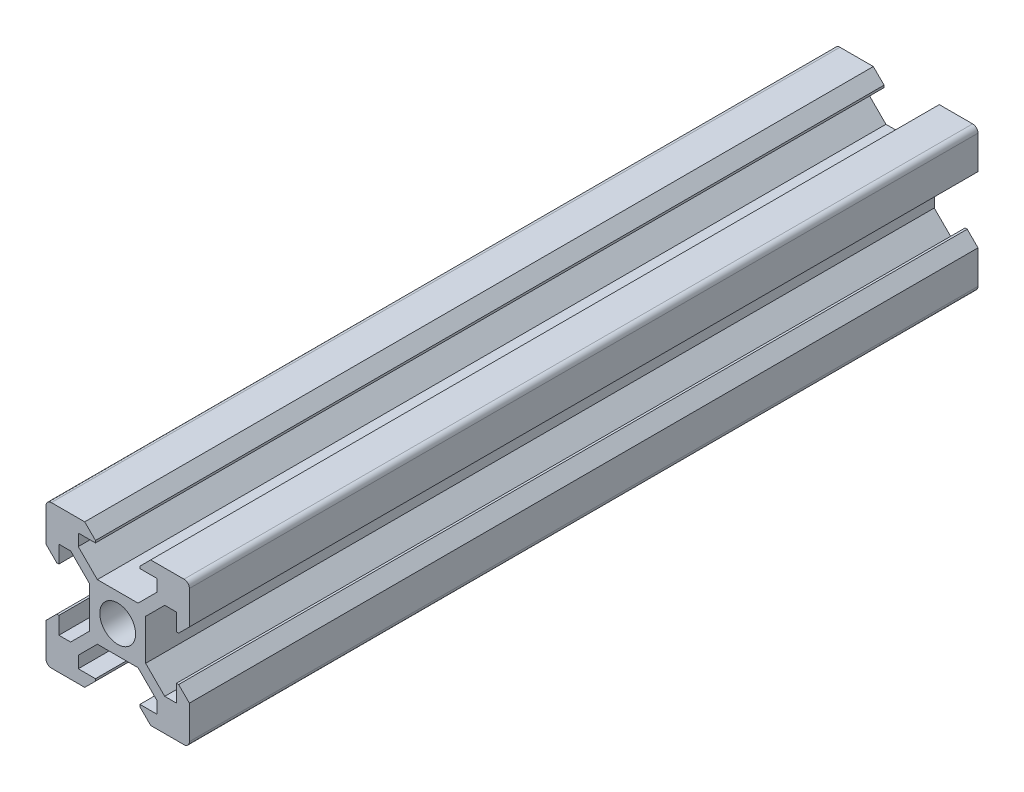
SolidWorks part; units mm, degrees
other "Markup1"
sketch "Sketch1" plane through (10, 10, 480) normal (0.5774, 0.5773, 0.5774) x (0.7071, 0, -0.7071)
ref_plane "Alzado" through (0, 0, 0) normal (0, 0, 1) x (1, 0, 0)
ref_plane "Planta" through (0, 0, 0) normal (0, 1, 0) x (1, 0, 0)
ref_plane "Vista lateral" through (0, 0, 0) normal (1, 0, 0) x (0, 0, -1)
sketch "Croquis1" plane through (0, 0, 0) normal (0, 0, 1) x (1, 0, 0)
  line L0 (-4.6, 10) -> (-3.1, 8.5)
  line L3 (-4.6, 10) -> (-9.25, 10)
  line L5 (-3.1, 8.5) -> (-3.1, 8.2)
  line L6 (-3.1, 8.2) -> (-5.5, 8.2)
  line L7 (-5.5, 8.2) -> (-5.5, 6.5607)
  line L8 (-5.5, 6.5607) -> (-2.84, 3.9007)
  line L9 (-2.84, 3.9007) -> (0, 3.9007)
  line L10 (0, 0) -> (-15.3499, 15.3499) construction
  line L11 (-3.9007, 2.84) -> (-3.9007, 0)
  line L12 (-6.5607, 5.5) -> (-3.9007, 2.84)
  line L13 (-8.2, 5.5) -> (-6.5607, 5.5)
  line L14 (-8.2, 3.1) -> (-8.2, 5.5)
  line L15 (-8.5, 3.1) -> (-8.2, 3.1)
  line L16 (-10, 4.6) -> (-10, 9.25)
  line L17 (-10, 4.6) -> (-8.5, 3.1)
  line L18 (10, 4.6) -> (8.5, 3.1)
  line L19 (10, 4.6) -> (10, 9.25)
  line L20 (8.5, 3.1) -> (8.2, 3.1)
  line L21 (8.2, 3.1) -> (8.2, 5.5)
  line L22 (8.2, 5.5) -> (6.5607, 5.5)
  line L23 (6.5607, 5.5) -> (3.9007, 2.84)
  line L24 (3.9007, 2.84) -> (3.9007, 0)
  line L25 (5.5, 6.5607) -> (2.84, 3.9007)
  line L26 (5.5, 8.2) -> (5.5, 6.5607)
  line L27 (3.1, 8.2) -> (5.5, 8.2)
  line L28 (3.1, 8.5) -> (3.1, 8.2)
  line L29 (4.6, 10) -> (9.25, 10)
  line L30 (4.6, 10) -> (3.1, 8.5)
  line L31 (2.84, 3.9007) -> (0, 3.9007)
  line L32 (4.6, -10) -> (3.1, -8.5)
  line L33 (4.6, -10) -> (9.25, -10)
  line L34 (3.1, -8.5) -> (3.1, -8.2)
  line L35 (3.1, -8.2) -> (5.5, -8.2)
  line L36 (5.5, -8.2) -> (5.5, -6.5607)
  line L37 (5.5, -6.5607) -> (2.84, -3.9007)
  line L38 (2.84, -3.9007) -> (0, -3.9007)
  line L39 (6.5607, -5.5) -> (3.9007, -2.84)
  line L40 (8.2, -5.5) -> (6.5607, -5.5)
  line L41 (8.2, -3.1) -> (8.2, -5.5)
  line L42 (8.5, -3.1) -> (8.2, -3.1)
  line L43 (10, -4.6) -> (10, -9.25)
  line L44 (10, -4.6) -> (8.5, -3.1)
  line L45 (3.9007, -2.84) -> (3.9007, 0)
  line L46 (-10, -4.6) -> (-8.5, -3.1)
  line L47 (-10, -4.6) -> (-10, -9.25)
  line L48 (-8.5, -3.1) -> (-8.2, -3.1)
  line L49 (-8.2, -3.1) -> (-8.2, -5.5)
  line L50 (-8.2, -5.5) -> (-6.5607, -5.5)
  line L51 (-6.5607, -5.5) -> (-3.9007, -2.84)
  line L52 (-3.9007, -2.84) -> (-3.9007, 0)
  line L53 (-5.5, -6.5607) -> (-2.84, -3.9007)
  line L54 (-5.5, -8.2) -> (-5.5, -6.5607)
  line L55 (-3.1, -8.2) -> (-5.5, -8.2)
  line L56 (-3.1, -8.5) -> (-3.1, -8.2)
  line L57 (-4.6, -10) -> (-9.25, -10)
  line L58 (-4.6, -10) -> (-3.1, -8.5)
  line L59 (-2.84, -3.9007) -> (0, -3.9007)
  circle A0 centre (0, 0) radius 2.5
  arc A1 (-9.25, 10) -> (-10, 9.25) centre (-9.25, 9.25) ccw
  arc A2 (10, 9.25) -> (9.25, 10) centre (9.25, 9.25) ccw
  arc A3 (9.25, -10) -> (10, -9.25) centre (9.25, -9.25) ccw
  arc A4 (-10, -9.25) -> (-9.25, -10) centre (-9.25, -9.25) ccw
  point P18 (-10, 10)
  point P37 (10, 10)
  point P55 (10, -10)
  point P73 (-10, -10)
  point P79 (0, 0)
  dimension "D1" = 5
  dimension "D5" = 0.75
  dimension "D2" = 10
  dimension "D3" = 10
  dimension "D4" = 4.6
  dimension "D6" = 5.5
  dimension "D7" = 135
  dimension "D8" = 0.75
  dimension "D9" = 225
  dimension "D10" = 2.84
  dimension "D11" = 1.8
  dimension "D12" = 3.1
  dimension "D13" = 4
extrude "Saliente-Extruir1" add sketch "Croquis1" along normal blind 110
